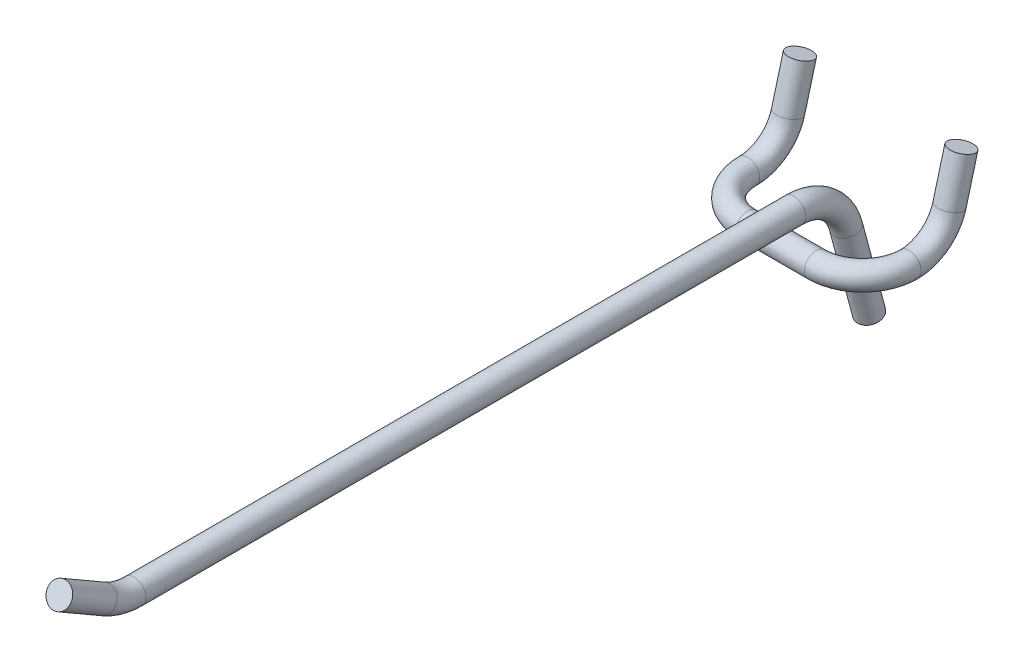
SolidWorks part; units mm, degrees
ref_plane "Front Plane" through (0, 0, 0) normal (0, 0, 1) x (1, 0, 0)
ref_plane "Top Plane" through (0, 0, 0) normal (0, 1, 0) x (1, 0, 0)
ref_plane "Right Plane" through (0, 0, 0) normal (1, 0, 0) x (0, 0, -1)
sketch "Sketch1" plane through (0, 0, 0) normal (1, 0, 0) x (0, 0, -1)
  line L0 (-51.9096, 0) -> (51.9096, 0)
  line L1 (-57.5992, 1.5245) -> (-64.6096, 5.572)
  line L2 (0, 3.7592) -> (-51.9096, 3.7592) construction
  line L3 (58.264, -4.8759) -> (61.9343, -18.5737)
  line L4 (50.03, -1.8796) -> (57.334, -1.8796)
  line L5 (63.6885, 2.9963) -> (65.5654, 10.0012)
  line L6 (62.1558, -4.8759) -> (65.5654, -17.6008)
  line L7 (61.9343, -18.5737) -> (65.5654, -17.6008) construction
  line L8 (-64.6096, -18.5738) -> (61.9343, -18.5737) construction
  arc A0 (-51.9096, 0) -> (-57.5992, 1.5245) centre (-51.9096, 11.3792) cw
  circle A1 centre (0, 1.8796) radius 1.8796
  arc A2 (-51.9096, 3.7592) -> (-51.9096, 18.9992) centre (-51.9096, 11.3792) cw construction
  arc A3 (51.9096, 0) -> (58.264, -4.8759) centre (51.9096, -6.5786) cw
  circle A4 centre (50.03, -1.8796) radius 1.8796
  arc A5 (57.334, -1.8796) -> (63.6885, 2.9963) centre (57.334, 4.699) ccw
  circle A6 centre (60.0796, -4.3895) radius 1.8796
  point P26 (0, -18.5737)
  point P34 (51.9096, -1.8796)
  dimension "Wire Diameter" = 3.7592
  dimension "D4" = 7.62
  dimension "D8" = 6.5786
  dimension "D1" = 30
  dimension "A" = 12.7
  dimension "D5" = 105
  dimension "D6" = 105
  dimension "Length" = 117.475
  dimension "D2" = 28.575
  dimension "D7" = 18.5738
  dimension "Projection" = 130.175
sketch "Sketch2" plane through (0, 0, 0) normal (0, 1, 0) x (1, 0, 0)
  line L0 (-12.7, 65.5654) -> (12.7, 65.5654)
  dimension "Center to Center Width" = 25.4
ref_plane "Plane1" through (0, -32.8131, -8.7923) normal (0, -0.9659, -0.2588) x (0, 0.2588, -0.9659)
sketch "Sketch11" plane through (0, -32.8131, -8.7923) normal (0, -0.9659, -0.2588) x (0, 0.2588, -0.9659)
  line L0 (55.0167, 0) -> (58.7759, 0) construction
  circle A0 centre (56.8963, 0) radius 1.8796
sketch "Sketch3" plane through (0, 0, 0) normal (1, 0, 0) x (0, 0, -1)
  line L0 (58.264, -4.8759) -> (61.9343, -18.5737) construction
  line L1 (-51.9096, 0) -> (51.9096, 0) construction
  line L2 (-57.5992, 1.5245) -> (-64.6096, 5.572) construction
  line L3 (58.264, -4.8759) -> (61.9343, -18.5737)
  line L4 (-51.9096, 0) -> (51.9096, 0)
  line L5 (-57.5992, 1.5245) -> (-64.6096, 5.572)
  arc A0 (58.264, -4.8759) -> (51.9096, 0) centre (51.9096, -6.5786) ccw construction
  arc A1 (-57.5992, 1.5245) -> (-51.9096, 0) centre (-51.9096, 11.3792) ccw construction
  arc A2 (58.264, -4.8759) -> (51.9096, 0) centre (51.9096, -6.5786) ccw
  arc A3 (-57.5992, 1.5245) -> (-51.9096, 0) centre (-51.9096, 11.3792) ccw
sweep "Sweep1" add profiles "Sketch11" path "Sketch3"
sketch "Sketch4" plane through (0, 0, 0) normal (1, 0, 0) x (0, 0, -1)
  line L0 (63.6885, 2.9963) -> (65.5654, 10.0012) construction
  line L1 (50.03, -1.8796) -> (57.334, -1.8796) construction
  line L2 (63.6885, 2.9963) -> (65.5654, 10.0012)
  line L3 (50.03, -1.8796) -> (57.334, -1.8796)
  arc A0 (57.334, -1.8796) -> (63.6885, 2.9963) centre (57.334, 4.699) ccw construction
  arc A1 (57.334, -1.8796) -> (63.6885, 2.9963) centre (57.334, 4.699) ccw
surface "Surface-Extrude1" sketch "Sketch4" parameters "D1"=25.4
ref_plane "Plane2" through (0, 10.0012, 0) normal (0, 1, 0) x (1, 0, 0)
sketch "Sketch6" plane through (0, 10.0012, 0) normal (0, 1, 0) x (1, 0, 0)
  line L0 (-12.7, 65.5654) -> (-12.7, 57.334)
  line L1 (12.7, 50.03) -> (-12.7, 50.03) construction
  line L2 (-5.3959, 50.03) -> (5.3959, 50.03)
  line L3 (0, 48.1504) -> (0, 51.9096) construction
  line L4 (0, 50.03) -> (0, 65.5654) construction
  line L5 (12.7, 65.5654) -> (12.7, 57.334)
  arc A0 (-12.7, 57.334) -> (-5.3959, 50.03) centre (-5.3959, 57.334) ccw
  arc A1 (12.7, 57.334) -> (5.3959, 50.03) centre (5.3959, 57.334) cw
curve "Curve2"
sweep "Sweep2" add path "Curve2" circular profile diameter 3.7592 parameters "D3"=3.7592
delete or keep bodies "Body-Delete/Keep 1" type delete bodies bodies 135
equation "\"D6@Sketch1\"=\"D5@Sketch1\""
equation "\"D7@Sketch1\"=\"D2@Sketch1\"*0.65"
equation "\"D8@Sketch1\" = \"Wire Diameter@Sketch1\" * 1.75"
equation "\"D1@Surface-Extrude1\" = \"Center to Center Width@Sketch2\""
